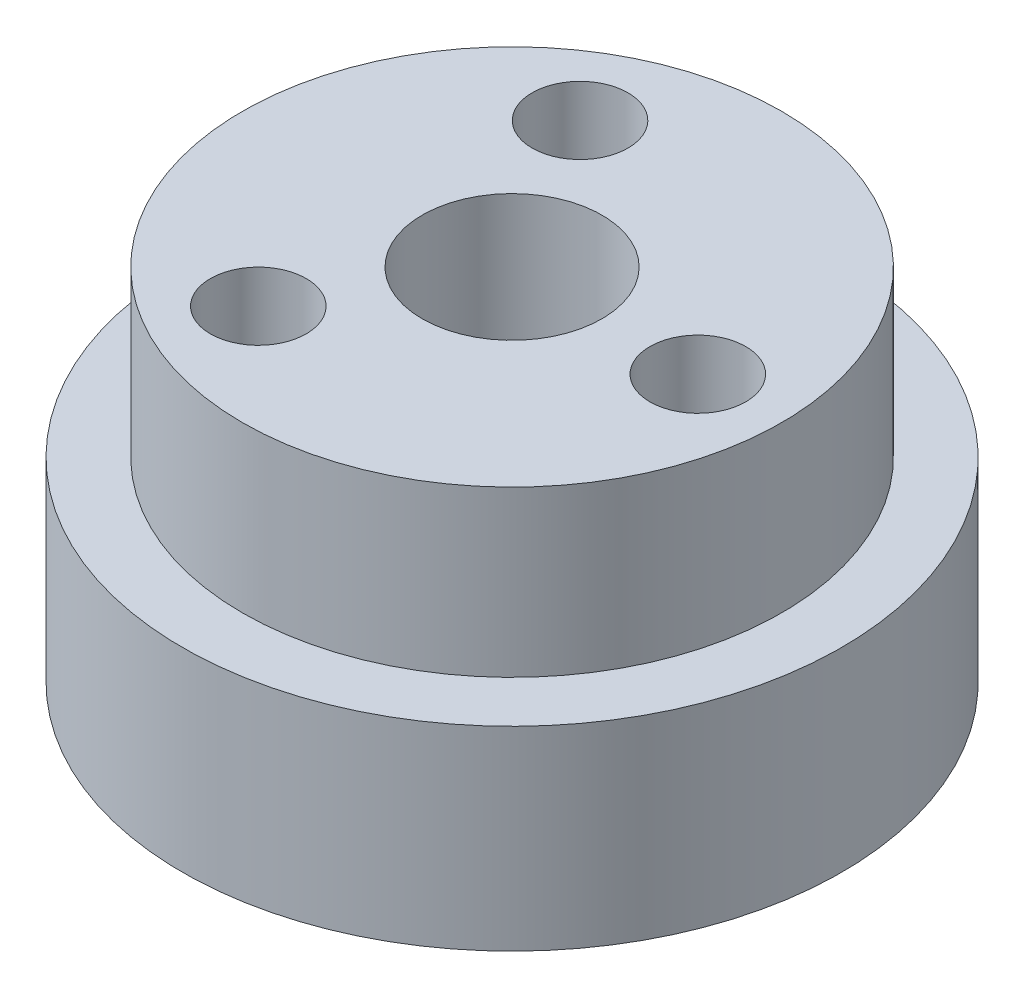
SolidWorks part; units mm, degrees
material "1060 Alloy"
ref_plane "Front Plane" through (0, 0, 0) normal (0, 0, 1) x (1, 0, 0)
ref_plane "Top Plane" through (0, 0, 0) normal (0, 1, 0) x (1, 0, 0)
ref_plane "Right Plane" through (0, 0, 0) normal (1, 0, 0) x (0, 0, -1)
sketch "Sketch1" plane through (0, 0, 0) normal (0, 1, 0) x (1, 0, 0)
  circle A0 centre (-22.1201, 12.8238) radius 11
  dimension "D1" = 22
extrude "Boss-Extrude1" add sketch "Sketch1" along normal blind 6.5
sketch "Sketch2" plane through (0, 6.5, 0) normal (0, 1, 0) x (1, 0, 0)
  circle A0 centre (-22.1201, 12.8238) radius 9
  dimension "D1" = 18
extrude "Boss-Extrude2" add sketch "Sketch2" along normal blind 5.5
sketch "Sketch3" plane through (0, 12, 0) normal (0, 1, 0) x (1, 0, 0)
  circle A0 centre (-22.1201, 12.8238) radius 3
  dimension "D1" = 6
extrude "Cut-Extrude1" cut sketch "Sketch3" against normal blind 15.5
sketch "Sketch4" plane through (0, 12, 0) normal (0, 1, 0) x (1, 0, 0)
  line L0 (-38.7288, 12.8238) -> (-4.8499, 12.8238) construction
  circle A0 centre (-15.9201, 12.8238) radius 1.6
  point P2 (-22.1201, 12.8238)
  dimension "D2" = 3.2
  dimension "D1" = 0
  dimension "D3" = 6.2
extrude "Cut-Extrude2" cut sketch "Sketch4" against normal blind 15.5
pattern_circular "CirPattern1" count 3 over 360 about axis through (-22.1201, 0, -12.8238) along (0, 1, 0) of "Cut-Extrude2"
